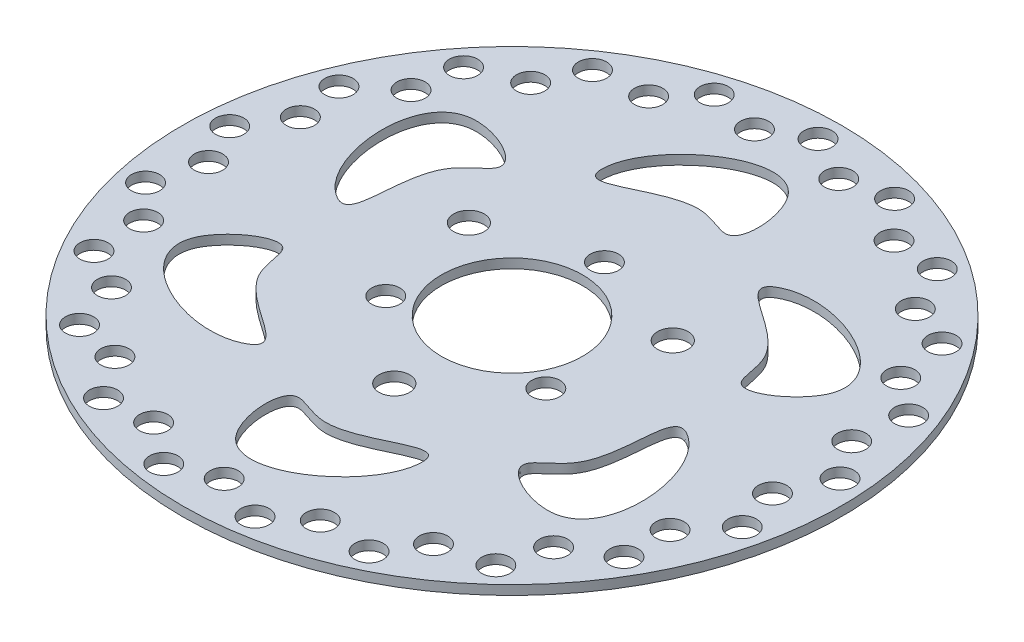
SolidWorks part; units mm, degrees
ref_plane "Front Plane" through (0, 0, 0) normal (0, 0, 1) x (1, 0, 0)
ref_plane "Top Plane" through (0, 0, 0) normal (0, 1, 0) x (1, 0, 0)
ref_plane "Right Plane" through (0, 0, 0) normal (1, 0, 0) x (0, 0, -1)
sketch "Sketch1" plane through (0, 0, 0) normal (0, 1, 0) x (1, 0, 0)
  line L0 (69.2378, -3.3965) -> (150.5455, -3.3965) construction
  line L1 (18.2061, 54.6183) -> (91.0306, 54.6183) construction
  line L2 (0, -1000) -> (0, 49000) construction
  line L3 (-866.0254, -500) -> (42435.2448, 24500) construction
  circle A0 centre (0, 0) radius 70
  circle A7 centre (0, 65) radius 3
  circle A8 centre (19.1591, 62.1122) radius 3
  circle A9 centre (36.6158, 53.7055) radius 3
  circle A10 centre (50.819, 40.5268) radius 3
  circle A11 centre (60.5068, 23.7472) radius 3
  circle A12 centre (64.8182, 4.8575) radius 3
  circle A13 centre (63.3703, -14.4639) radius 3
  circle A14 centre (56.2917, -32.5) radius 3
  circle A15 centre (44.2112, -47.6484) radius 3
  circle A16 centre (28.2024, -58.563) radius 3
  circle A17 centre (9.6877, -64.274) radius 3
  circle A18 centre (-9.6877, -64.274) radius 3
  circle A19 centre (-28.2024, -58.563) radius 3
  circle A20 centre (-44.2112, -47.6484) radius 3
  circle A21 centre (-56.2917, -32.5) radius 3
  circle A22 centre (-8.5, 60) radius 3
  circle A23 centre (9.5629, 59.8398) radius 3
  circle A24 centre (26.7762, 54.3625) radius 3
  circle A25 centre (41.6102, 44.055) radius 3
  circle A26 centre (52.747, 29.8329) radius 3
  circle A27 centre (59.197, 12.96) radius 3
  circle A28 centre (60.3871, -5.0644) radius 3
  circle A29 centre (56.2115, -22.6388) radius 3
  circle A30 centre (47.0413, -38.2016) radius 3
  circle A31 centre (33.6913, -50.3701) radius 3
  circle A32 centre (17.3476, -58.063) radius 3
  circle A33 centre (-0.5375, -60.5967) radius 3
  circle A34 centre (-18.3748, -57.7461) radius 3
  circle A35 centre (-34.5794, -49.7646) radius 3
  circle A36 centre (-47.7115, -37.3612) radius 3
  circle A37 centre (0, 0) radius 15
  circle A38 centre (0, 0) radius 19.6299 construction
  circle A39 centre (0, 19.6299) radius 3
  circle A40 centre (17, -9.815) radius 3
  circle A41 centre (-17, -9.815) radius 3
  circle A42 centre (-63.3703, -14.4639) radius 3
  circle A43 centre (-64.8182, 4.8575) radius 3
  circle A44 centre (-60.5068, 23.7472) radius 3
  circle A45 centre (-50.819, 40.5268) radius 3
  circle A46 centre (-36.6158, 53.7055) radius 3
  circle A47 centre (-19.1591, 62.1122) radius 3
  circle A48 centre (-56.6042, -21.6381) radius 3
  circle A49 centre (-60.4674, -3.9924) radius 3
  circle A50 centre (-58.9578, 14.008) radius 3
  circle A51 centre (-52.2096, 30.7638) radius 3
  circle A52 centre (-40.8222, 44.7861) radius 3
  circle A53 centre (-25.8077, 54.8289) radius 3
  circle A54 centre (0, 0) radius 25 construction
  circle A55 centre (21.6506, 12.5) radius 3.25
  circle A56 centre (0, -25) radius 3.25
  circle A57 centre (0, 0) radius 25 construction
  circle A58 centre (-21.6506, 12.5) radius 3.25
  circle A59 centre (0, 0) radius 25 construction
  point P16 (0, 0)
  point P50 (0, 0)
  point P82 (0, 0)
  point P117 (0, 0)
  dimension "D1" = 140
  dimension "D2" = 6
  dimension "D3" = 3
  dimension "D5" = 50
  dimension "D6" = 6
  dimension "D12" = 30
  dimension "D13" = 6.5
  dimension "D4" = 34
  dimension "D7" = 65
  dimension "D9" = 5
  dimension "D10" = 8.5
  dimension "D14" = 60
  dimension "D8" = 21
  dimension "D11" = 21
  dimension "D15" = 3
extrude "Body" add sketch "Sketch1" along normal blind 2
sketch "Sketch3" plane through (0, 2, 0) normal (0, 1, 0) x (1, 0, 0)
  spline S0 degree 3 poles (36.5679, 24.3143) (35.0603, 7.0588) (61.1988, 25.0299) (31.8912, 38.4036) (16.9948, 30.0173) (36.5679, 24.3143) (35.0603, 7.0588) (61.1988, 25.0299) knots -0.39669 -0.374741 -0.109929 0 0.195832 0.60331 0.625259 0.890071 1 1.195832 1.60331 1.625259 only from (36.8401, 11.8478) to (36.8401, 11.8478)
  spline S1 degree 3 poles (39.3408, -19.5116) (23.6433, -26.8337) (52.2759, -40.4848) (49.2041, -8.4168) (34.4932, 0.2908) (39.3408, -19.5116) (23.6433, -26.8337) (52.2759, -40.4848) knots -0.39669 -0.374741 -0.109929 0 0.195832 0.60331 0.625259 0.890071 1 1.195832 1.60331 1.625259 only from (28.6806, -25.9805) to (28.6806, -25.9805)
  spline S2 degree 3 poles (2.7729, -43.8259) (-11.417, -33.8925) (-8.9229, -65.5147) (17.3129, -46.8204) (17.4984, -29.7266) (2.7729, -43.8259) (-11.417, -33.8925) (-8.9229, -65.5147) knots -0.39669 -0.374741 -0.109929 0 0.195832 0.60331 0.625259 0.890071 1 1.195832 1.60331 1.625259 only from (-8.1595, -37.8284) to (-8.1595, -37.8284)
  spline S3 degree 3 poles (-2.7729, 43.8259) (11.417, 33.8925) (8.9229, 65.5147) (-17.3129, 46.8204) (-17.4984, 29.7266) (-2.7729, 43.8259) (11.417, 33.8925) (8.9229, 65.5147) knots -0.39669 -0.374741 -0.109929 0 0.195832 0.60331 0.625259 0.890071 1 1.195832 1.60331 1.625259 only from (8.1595, 37.8284) to (8.1595, 37.8284)
  spline S4 degree 3 poles (-36.5679, -24.3143) (-35.0603, -7.0588) (-61.1988, -25.0299) (-31.8912, -38.4036) (-16.9948, -30.0173) (-36.5679, -24.3143) (-35.0603, -7.0588) (-61.1988, -25.0299) knots -0.39669 -0.374741 -0.109929 0 0.195832 0.60331 0.625259 0.890071 1 1.195832 1.60331 1.625259 only from (-36.8401, -11.8478) to (-36.8401, -11.8478)
  spline S5 degree 3 poles (-39.3408, 19.5116) (-23.6433, 26.8337) (-52.2759, 40.4848) (-49.2041, 8.4168) (-34.4932, -0.2908) (-39.3408, 19.5116) (-23.6433, 26.8337) (-52.2759, 40.4848) knots -0.39669 -0.374741 -0.109929 0 0.195832 0.60331 0.625259 0.890071 1 1.195832 1.60331 1.625259 only from (-28.6806, 25.9805) to (-28.6806, 25.9805)
  point P33 (0, 0)
extrude "Holes" cut sketch "Sketch3" against normal through all
